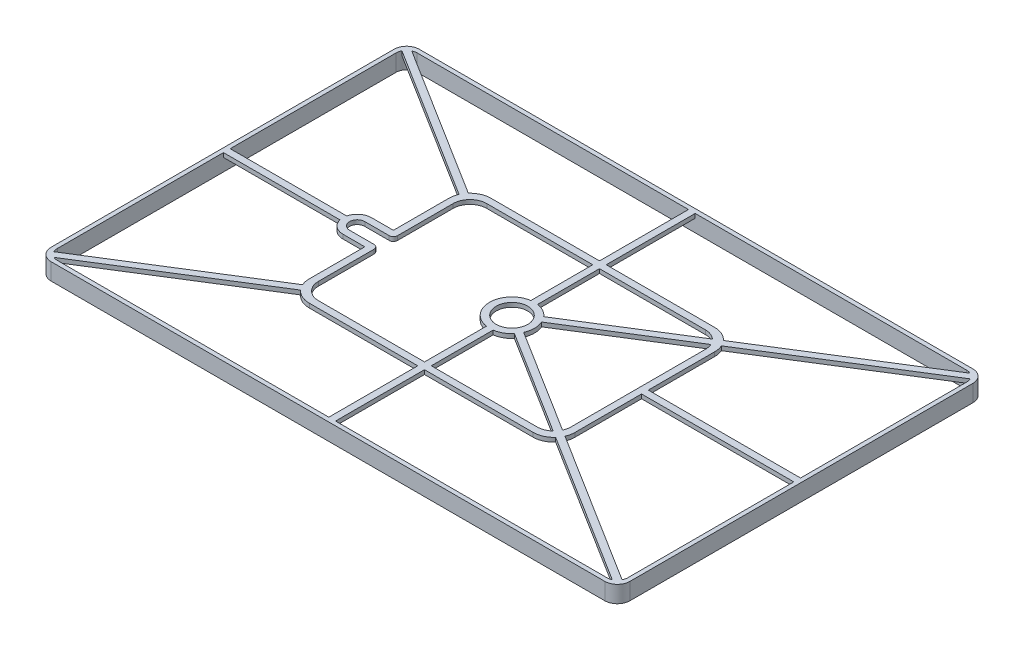
SolidWorks part; units mm, degrees
ref_plane "Front Plane" through (0, 0, 0) normal (0, 0, 1) x (1, 0, 0)
ref_plane "Top Plane" through (0, 0, 0) normal (0, 1, 0) x (1, 0, 0)
ref_plane "Right Plane" through (0, 0, 0) normal (1, 0, 0) x (0, 0, -1)
sketch "Esquisse1" plane through (0, 0, 0) normal (0, 1, 0) x (1, 0, 0)
  line L1 (-65.3, 42.75) -> (65.3, 42.75)
  line L2 (-67.8, 40.25) -> (-67.8, -40.25)
  line L3 (-65.3, -42.75) -> (65.3, -42.75)
  line L4 (67.8, 40.25) -> (67.8, -40.25)
  line L5 (-67.8, 42.75) -> (67.8, -42.75) construction
  line L6 (-67.8, -42.75) -> (67.8, 42.75) construction
  line L7 (-65.8, 43.75) -> (65.8, 43.75)
  line L8 (-68.8, 40.75) -> (-68.8, -40.75)
  line L9 (-65.8, -43.75) -> (65.8, -43.75)
  line L10 (68.8, 40.75) -> (68.8, -40.75)
  arc A0 (-67.8, -40.25) -> (-65.3, -42.75) centre (-65.3, -40.25) ccw
  arc A1 (65.3, -42.75) -> (67.8, -40.25) centre (65.3, -40.25) ccw
  arc A2 (65.3, 42.75) -> (67.8, 40.25) centre (65.3, 40.25) cw
  arc A3 (-65.3, 42.75) -> (-67.8, 40.25) centre (-65.3, 40.25) ccw
  arc A4 (65.8, -43.75) -> (68.8, -40.75) centre (65.8, -40.75) ccw
  arc A5 (-68.8, -40.75) -> (-65.8, -43.75) centre (-65.8, -40.75) ccw
  arc A6 (-65.8, 43.75) -> (-68.8, 40.75) centre (-65.8, 40.75) ccw
  arc A7 (65.8, 43.75) -> (68.8, 40.75) centre (65.8, 40.75) cw
  point P0 (0, 0)
  dimension "D3" = 2.5
  dimension "D8" = 3
  dimension "D1" = 135.6
  dimension "D2" = 85.5
  dimension "D4" = 1
  dimension "D5" = 1
  dimension "D6" = 1
  dimension "D7" = 1
extrude "Boss.-Extru.1" add sketch "Esquisse1" along normal blind 4
sketch "Esquisse2" plane through (0, 4, 0) normal (0, 1, 0) x (1, 0, 0)
  line L0 (0, 0) -> (0, 42.75) construction
  line L1 (-26, 20) -> (-0.8, 20)
  line L2 (-30, 16) -> (-30, -16)
  line L3 (-26, -20) -> (-0.8, -20)
  line L4 (30, 16) -> (30, -16)
  line L5 (31.1854, 18.5935) -> (67.9172, 41.6059)
  line L6 (-30, -20) -> (30, 20) construction
  line L7 (-26.6, 21.6) -> (-0.8, 21.6)
  line L8 (-31.6, 16.6) -> (-31.6, 0.8)
  line L9 (-26.6, -21.6) -> (-0.8, -21.6)
  line L10 (31.6, 16.6) -> (31.6, 0.8)
  line L11 (65.3, 42.75) -> (-65.3, 42.75) construction
  line L12 (0, 0) -> (0, -42.75) construction
  line L13 (-65.3, -42.75) -> (65.3, -42.75) construction
  line L14 (0, 0) -> (67.8, 0) construction
  line L15 (67.8, -40.25) -> (67.8, 40.25) construction
  line L16 (0, 0) -> (-67.8, 0) construction
  line L17 (-67.8, 40.25) -> (-67.8, -40.25) construction
  line L18 (0, 0) -> (67.0678, 42.0178) construction
  line L19 (0, 0) -> (67.0678, -42.0178) construction
  line L20 (0, 0) -> (-67.0678, -42.0178) construction
  line L21 (0, 0) -> (-67.0678, 42.0178) construction
  line L22 (-68.3226, -0.8) -> (-68.3226, 0.8)
  line L24 (-0.8, 43.323) -> (-0.8, 21.6)
  line L26 (0.8, 43.323) -> (0.8, 21.6)
  line L27 (-0.4959, 43.323) -> (0.5344, 21.6) construction
  line L28 (-0.5344, 21.6) -> (0.4959, 43.323) construction
  line L29 (31.6, 0.8) -> (68.2846, 0.8)
  line L31 (31.6, -0.8) -> (68.2846, -0.8)
  line L33 (31.6, 0.4621) -> (68.2846, -0.6333) construction
  line L34 (31.6, -0.4621) -> (68.2846, 0.6333) construction
  line L36 (-0.8, -21.6) -> (-0.8, -43.2183)
  line L38 (0.8, -21.6) -> (0.8, -43.2183)
  line L39 (-0.4461, -21.6) -> (0.4618, -43.2183) construction
  line L40 (-0.4618, -43.2183) -> (0.4461, -21.6) construction
  line L41 (-31.6, -0.8) -> (-68.3226, -0.8)
  line L43 (-31.6, 0.8) -> (-68.3226, 0.8)
  line L45 (-31.6, -0.5779) -> (-68.3226, 0.5564) construction
  line L46 (-31.6, 0.5779) -> (-68.3226, -0.5564) construction
  line L47 (-0.8, -43.2183) -> (0.8, -43.2183)
  line L48 (30.3208, 19.94) -> (67.0678, 42.9618)
  line L49 (68.2846, 0.8) -> (68.2846, -0.8)
  line L50 (-0.8, 43.323) -> (0.8, 43.323)
  line L51 (-31.6, -0.8) -> (-31.6, -16.6)
  line L52 (0.8, 21.6) -> (26.6, 21.6)
  line L53 (31.6, -0.8) -> (31.6, -16.6)
  line L54 (0.8, -21.6) -> (26.6, -21.6)
  line L55 (30.3208, -19.94) -> (66.8721, -42.8392)
  line L56 (67.7216, -41.4834) -> (31.1854, -18.5935)
  line L57 (66.8721, -42.8392) -> (67.7216, -41.4834)
  line L58 (29.6516, 17.6326) -> (4.9075, 2.1305)
  line L59 (-67.9219, -41.6089) -> (-67.0725, -42.9647)
  line L60 (-67.0678, 42.9618) -> (-67.9172, 41.6059)
  line L61 (0, 0) -> (30, -20) construction
  line L62 (-25.2846, -16.7847) -> (-28.7173, -18.9353)
  line L63 (-31.1854, -18.5935) -> (-67.9219, -41.6089)
  line L64 (-30.3208, -19.94) -> (-67.0725, -42.9647)
  line L65 (-30.3208, 19.94) -> (-67.0678, 42.9618)
  line L66 (-31.1854, 18.5935) -> (-67.9172, 41.6059)
  line L67 (67.0678, 42.9618) -> (67.9172, 41.6059)
  line L68 (-0.8, 20) -> (-0.8, 5.2898)
  line L69 (0.8, 20) -> (0.8, 5.2898)
  line L70 (0.8, -20) -> (0.8, -5.2898)
  line L71 (-0.8, -20) -> (-0.8, -5.2898)
  line L72 (29.6516, -17.6326) -> (4.9075, -2.1305)
  line L73 (28.7173, -18.9353) -> (4.058, -3.4864)
  line L74 (28.7173, 18.9353) -> (4.058, 3.4864)
  line L75 (0.8, -20) -> (26, -20)
  line L76 (0.8, 20) -> (26, 20)
  arc A0 (-26, 20) -> (-30, 16) centre (-26, 16) ccw
  arc A1 (-30, -16) -> (-26, -20) centre (-26, -16) ccw
  arc A2 (26, -20) -> (28.7173, -18.9353) centre (26, -16) ccw
  arc A3 (26, 20) -> (28.7173, 18.9353) centre (26, 16) cw
  arc A4 (-31.6, -16.6) -> (-31.1854, -18.5935) centre (-26.6, -16.6) ccw
  arc A5 (26.6, -21.6) -> (30.3208, -19.94) centre (26.6, -16.6) ccw
  arc A6 (26.6, 21.6) -> (30.3208, 19.94) centre (26.6, 16.6) cw
  arc A7 (-26.6, 21.6) -> (-30.3208, 19.94) centre (-26.6, 16.6) ccw
  arc A8 (67.8, 40.25) -> (65.3, 42.75) centre (65.3, 40.25) ccw construction
  arc A9 (65.3, -42.75) -> (67.8, -40.25) centre (65.3, -40.25) ccw construction
  arc A10 (-67.8, -40.25) -> (-65.3, -42.75) centre (-65.3, -40.25) ccw construction
  arc A11 (-65.3, 42.75) -> (-67.8, 40.25) centre (-65.3, 40.25) ccw construction
  arc A12 (-30.3208, -19.94) -> (-26.6, -21.6) centre (-26.6, -16.6) ccw
  arc A13 (-31.1854, 18.5935) -> (-31.6, 16.6) centre (-26.6, 16.6) ccw
  arc A14 (31.1854, -18.5935) -> (31.6, -16.6) centre (26.6, -16.6) ccw
  arc A15 (31.1854, 18.5935) -> (31.6, 16.6) centre (26.6, 16.6) cw
  circle A16 centre (0, 0) radius 3.75
  arc A17 (4.5337, 2.8404) -> (4.4515, 2.9676) centre (0, 0) ccw
  arc A18 (4.058, 3.4864) -> (0.8, 5.2898) centre (0, 0) ccw
  arc A19 (0.8, -5.2898) -> (4.058, -3.4864) centre (0, 0) ccw
  arc A20 (29.6516, -17.6326) -> (30, -16) centre (26, -16) ccw
  arc A21 (4.4515, -2.9676) -> (4.5337, -2.8404) centre (0, 0) ccw
  arc A22 (4.9075, -2.1305) -> (4.9075, 2.1305) centre (0, 0) ccw
  arc A23 (29.6516, 17.6326) -> (30, 16) centre (26, 16) cw
  arc A24 (-0.8, 5.2898) -> (-0.8, -5.2898) centre (0, 0) ccw
  point P0 (0, 0)
  point P34 (0, 32.8678)
  point P64 (47.075, 0)
  point P69 (0, -32.2214)
  point P74 (-50.308, 0)
  line M41 (65.3, -42.75) -> (-65.3, -42.75)
  arc M42 (-65.3, -42.75) -> (-67.8, -40.25) centre (-65.3, -40.25) cw
  line M43 (-67.8, -40.25) -> (-67.8, 40.25)
  arc M44 (-67.8, 40.25) -> (-65.3, 42.75) centre (-65.3, 40.25) cw
  line M45 (-65.3, 42.75) -> (65.3, 42.75)
  arc M46 (65.3, 42.75) -> (67.8, 40.25) centre (65.3, 40.25) cw
  line M47 (67.8, 40.25) -> (67.8, -40.25)
  arc M48 (67.8, -40.25) -> (65.3, -42.75) centre (65.3, -40.25) cw
  dimension "D3" = 4
  dimension "D8" = 5
  dimension "D1" = 40
  dimension "D4" = 1.6
  dimension "D5" = 1.6
  dimension "D6" = 1.6
  dimension "D7" = 1.6
  dimension "D9" = 1.6
  dimension "D10" = 1.6
  dimension "D11" = 1.6
  dimension "D12" = 1.6
  dimension "D13" = 0.8
  dimension "D14" = 0.8
  dimension "D18" = 0.8
  dimension "D19" = 0.8
extrude "Boss.-Extru.3" add sketch "Esquisse2" against normal blind 1 contours A15 L5 L48 A6 L52 L26 L24 L7 A7 L65 L66 A13 L8 L43 L41 L51 A4 L63 L64 A12 L9 L36 L38 L54 A5 L55 L56 A14 L53 L31 L29 L10 L1 A3 L4 A2 L3 A1 L2 A0 M46 M45 M44 M43 M42 M41 M48 M47
sketch "Esquisse3" plane through (0, 4, 0) normal (0, 1, 0) x (1, 0, 0)
  line L0 (-30, 16) -> (-30, -16) construction
  line L1 (-36.8, 1.8) -> (-33.9156, 1.8)
  line L3 (-36.8, -1.8) -> (-33.9156, -1.8)
  line L5 (-36.8, 1.8) -> (-30, 0) construction
  line L6 (-36.8, -1.8) -> (-30, 0) construction
  line L7 (-30, 0) -> (-36.8, 0) construction
  line L8 (-31.6, 7.2461) -> (-30, 7.2461)
  line L12 (-36.8, 3.4) -> (-31.6, 3.4)
  line L13 (-31.6, 16.6) -> (-31.6, 0.8) construction
  line L14 (-31.6, 3.4) -> (-31.6, 7.2461)
  line L15 (-30, 7.2461) -> (-30, -10.7102)
  line L16 (-36.8, -3.4) -> (-31.6, -3.4)
  line L17 (-31.6, -0.8) -> (-31.6, -16.6) construction
  line L18 (-31.6, -3.4) -> (-31.6, -10.7102)
  line L19 (-31.6, -10.7102) -> (-30, -10.7102)
  line L20 (-33.9156, 1.8) -> (-31.6, 1.8)
  line L22 (-33.9156, -1.8) -> (-31.6, -1.8)
  line L23 (-31.6, 1.8) -> (-31.6, -1.8)
  arc A0 (-36.8, 1.8) -> (-36.8, -1.8) centre (-36.8, 0) ccw
  arc A2 (-36.8, 3.4) -> (-36.8, -3.4) centre (-36.8, 0) ccw
  point P0 (-30, 0)
  dimension "D1" = 3.6
  dimension "D2" = 6.8
extrude "Boss.-Extru.4" add sketch "Esquisse3" against normal blind 1
sketch "Esquisse4" plane through (0, 4, 0) normal (0, 1, 0) x (1, 0, 0)
  line L0 (-36.8, 1.8) -> (-28.2305, 1.8)
  line L1 (-28.2305, 1.8) -> (-28.2305, -1.8)
  line L2 (-28.2305, -1.8) -> (-36.8, -1.8)
  arc A0 (-36.8, 1.8) -> (-36.8, -1.8) centre (-36.8, 0) ccw
extrude "Enlèv. mat.-Extru.1" cut sketch "Esquisse4" against normal through all
fillet "Congé1" radius 1 2 edges at (-30, 3.5, 1.8) (-30, 3.5, -1.8)
